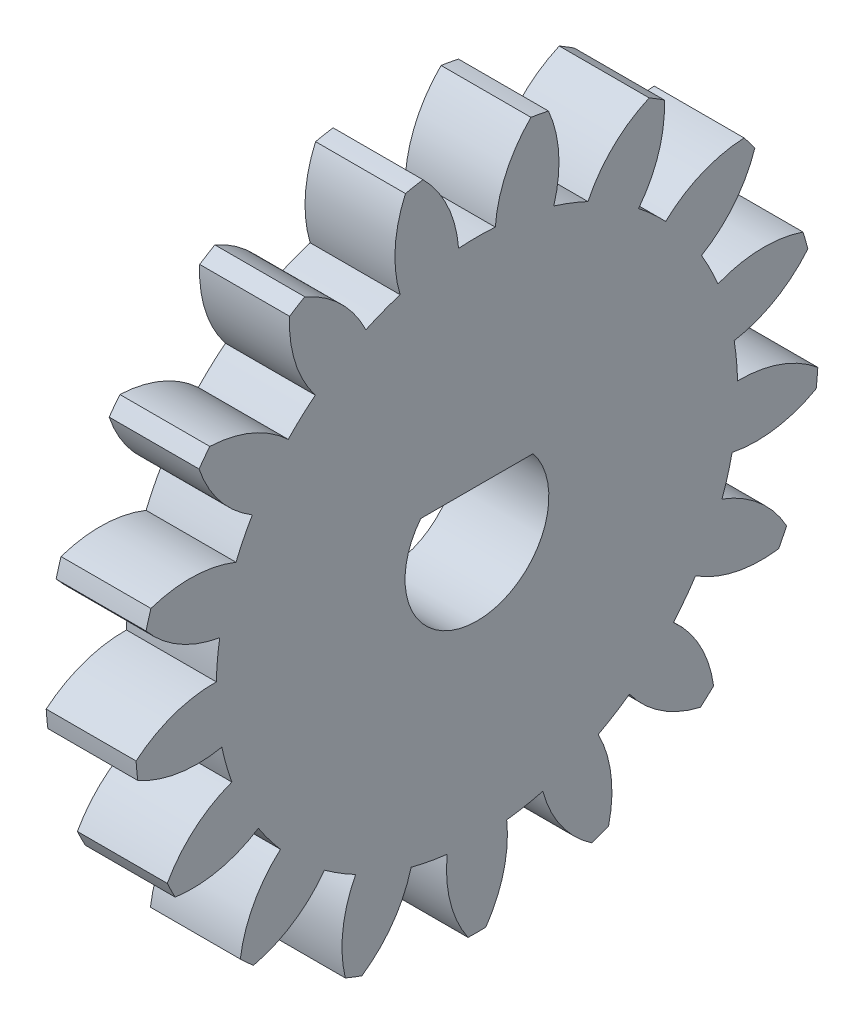
SolidWorks part; units mm, degrees
ref_plane "Plane1" through (0, 0, 0) normal (0, 0, 1) x (1, 0, 0)
ref_plane "Plane2" through (0, 0, 0) normal (0, 1, 0) x (1, 0, 0)
ref_plane "Plane3" through (0, 0, 0) normal (1, 0, 0) x (0, 0, -1)
sketch "HoldingSke" plane through (0, 0, 0) normal (0, 1, 0) x (1, 0, 0)
  line L0 (0, 0) -> (0.4782, -0.1462)
  line L1 (-15, 0) -> (100, 0) construction
  line L2 (0, 0) -> (-2.1039, 2.3779)
  line L3 (0, 0) -> (-11.863, 4.5341)
  line L4 (0, 0) -> (8.2586, 2.5249)
  line L5 (0, 0) -> (-46.8476, -17.4728)
  line L6 (0, 0) -> (-4.1448, -2.7965)
  line L7 (-2.1039, 2.3779) -> (8.6586, 51.2059)
  line L8 (-76.2, 54.61) -> (-74.8, 54.61)
  line L9 (-71.009, 38.7566) -> (-53.1078, 45.2721)
  line L10 (-76.2, 71.12) -> (104.1128, 71.12)
  line L11 (0, 0) -> (-5, 0)
  line L12 (-76.2, 101.6) -> (-76.133, 101.6)
  line L13 (24.9733, 27.94) -> (52.9518, 28.4284)
  line L14 (24.9733, 27.94) -> (24.9743, 27.94)
  line L15 (24.9733, 27.94) -> (100.4006, 29.5858)
  line L16 (-63.627, -2) -> (-12.827, -2)
  circle A0 centre (0, 0) radius 4
  circle A1 centre (0, 0) radius 14.499
  circle A2 centre (0, 0) radius 37.5
  circle A3 centre (0, 0) radius 4
  dimension "MHD" = 28.998
  dimension "Hub_dia" = 75
  dimension "Bore" = 8
  dimension "MBD" = 8
  dimension "Num_teeth" = 17
  dimension "Pitch" = 0.5
  dimension "Overall_len" = 50
  dimension "Show_teeth" = 17
  dimension "Thickness" = 5
  dimension "OAL" = 50.0001
  dimension "T_dim" = 1.4
  dimension "Ap" = 20
  dimension "H" = 19.05
  dimension "Pitch_radius" = 180.3128
  dimension "Width" = 5
  dimension "Backlash" = 0.067
  dimension "Addendum_fac" = 1
  dimension "Dedendum_fac" = 1.25
  dimension "Clearance_fac" = 0.25
  dimension "Dedendum_add" = 0.001
  dimension "Module" = 2
sketch "BasProSke" plane through (0, 0, 0) normal (0, 1, 0) x (1, 0, 0)
  line L0 (-10, 0) -> (60, 0) construction
  line L1 (0, 0) -> (0, 19)
  line L2 (0, 0) -> (5, 0)
  line L3 (5, 0) -> (5, 19)
  line L4 (5, 19) -> (0, 19)
  dimension "Thickness" = 5
  dimension "Diameter" = 38
revolve "Base-Revolve" add sketch "BasProSke" angle 360 about L0
sketch "TooCutSke" plane through (0, 0, 0) normal (1, 0, 0) x (0, 0, -1)
  line L1 (0, 0) -> (0, 107) construction
  line L2 (0, 0) -> (-1.6857, 16.9162) construction
  line L3 (0, 0) -> (-6.2247, 33.2991) construction
  line L4 (-1.6857, 16.9162) -> (-3.1123, 16.6495) construction
  arc A0 (1.0204, 14.4631) -> (-1.0204, 14.4631) centre (0, 0) ccw
  arc A1 (3.0261, 18.7832) -> (-3.0261, 18.7832) centre (0, 0) ccw
  circle A2 centre (0, 0) radius 17 construction
  circle A3 centre (0, 0) radius 15.9748 construction
  arc A4 (-1.0204, 14.4631) -> (-3.0261, 18.7832) centre (-7.8003, 13.9409) ccw
  arc A5 (3.0261, 18.7832) -> (1.0204, 14.4631) centre (7.8003, 13.9409) ccw
  dimension "Root_dia" = 28.998
  dimension "Overcut_dia" = 38.0508
  dimension "Pitch_dia" = 34
  dimension "Base_dia" = 31.9495
  dimension "Flank_rad" = 6.8
  dimension "Half_ang" = 10.588
  dimension "Half_CT" = 1.4513
extrude "ToothCut" cut sketch "TooCutSke" along normal through all
fillet "Breaks" [suppressed] radius 0.04
fillet "RootFillets" [suppressed] radius 0.501
pattern_circular "TeethCuts" count 17 every 21.176 about axis through (-10, 0, 0) along (1, 0, 0) of "ToothCut", "RootFillets", "Breaks"
sketch "HubNeaOneSke" plane through (0, 0, 0) normal (-1, 0, 0) x (0, 0, 1)
  circle A0 centre (0, 0) radius 14.499
  dimension "Diameter" = 28.998
extrude "HubNearOne" [suppressed] add sketch "HubNeaOneSke" along normal blind 45.0001
sketch "HubNeaBotSke" plane through (0, 0, 0) normal (-1, 0, 0) x (0, 0, 1)
  circle A0 centre (0, 0) radius 14.499
  dimension "Diameter" = 28.998
extrude "HubNearBoth" [suppressed] add sketch "HubNeaBotSke" along normal blind 22.5
ref_plane "FarPln" through (5, 0, 0) normal (1, 0, 0) x (0, 0, -1)
sketch "HubFarSke" plane through (5, 0, 0) normal (1, 0, 0) x (0, 0, -1)
  circle A0 centre (0, 0) radius 14.499
  dimension "Diameter" = 28.998
extrude "HubFar" [suppressed] add sketch "HubFarSke" along normal blind 22.5
sketch "BorSke" plane through (0, 0, 0) normal (1, 0, 0) x (0, 0, -1)
  circle A0 centre (0, 0) radius 4
  dimension "Diameter" = 8
extrude "Bore" cut sketch "BorSke" along normal mid plane 100.0001
sketch "KeySke" plane through (0, 0, 0) normal (1, 0, 0) x (0, 0, -1)
  line L0 (-1.5, 0) -> (-1.5, 5.4)
  line L1 (-1.5, 5.4) -> (1.5, 5.4)
  line L2 (1.5, 5.4) -> (1.5, 0)
  line L3 (0, 0) -> (0, 34) construction
  line L4 (-1.5, 0) -> (1.5, 0)
  dimension "Offset" = 5.4
  dimension "Width" = 3
extrude "Keyway" [suppressed] cut sketch "KeySke" along normal mid plane 100.0001
pattern_circular "Keyway2" [suppressed] count 2 every 90 about axis through (-10, 0, 0) along (1, 0, 0)
sketch "Sketch1" plane through (0, 0, 0) normal (-1, 0, 0) x (0, 0, 1)
  line L0 (-3.1225, 2.5) -> (3.1225, 2.5)
  circle A0 centre (0, 0) radius 4
  dimension "D2" = 8
  dimension "D1" = 2.5
extrude "Boss-Extrude1" add sketch "Sketch1" against normal blind 5 contours L0 A0
equation "' \"Module@HoldingSke\" = 6.35"
equation "' \"Num_teeth@HoldingSke\" = 12"
equation "' \"Ap@HoldingSke\" =  20"
equation "' \"Ap@HoldingSke\" = 20"
equation "' \"Width@HoldingSke\" = 0.5 * 25.4"
equation "' \"Hub_dia@HoldingSke\"= 1 * 25.4"
equation "' \"Hub_dia@HoldingSke\" = 1 * 25.4"
equation "' \"Overall_len@HoldingSke\" = 1.0 * 25.4"
equation "' \"Bore@HoldingSke\" = 0.75 * 25.4"
equation "' \"T_dim@HoldingSke\" = 0.1 * 25.4"
equation "' \"Width@KeySke\" = 0.25 * 25.4"
equation "' \"Show_teeth@HoldingSke\" = 13"
equation "' \"Backlash@HoldingSke\" = 0.009 * 25.4"
equation "' \"Addendum_fac@HoldingSke\" = 1.0"
equation "' \"Dedendum_fac@HoldingSke\" = 1.25"
equation "' \"Dedendum_add@HoldingSke\" = 0.00005 * 25.4"
equation "' \"Clearance_fac@HoldingSke\" = 0.25"
equation "\"Pitch@HoldingSke\" = 1 / \"Module@HoldingSke\""
equation "\"Overcut_dia@TooCutSke\" = (\"Num_teeth@HoldingSke\" + 2 * \"Addendum_fac@HoldingSke\") / \"Pitch@HoldingSke\" + 0.002 * 25.4"
equation "\"Pitch_dia@TooCutSke\" = \"Num_teeth@HoldingSke\" / \"Pitch@HoldingSke\""
equation "\"Base_dia@TooCutSke\" = \"Num_teeth@HoldingSke\" / \"Pitch@HoldingSke\" * cos((\"Ap@HoldingSke\"  * 3.14159265 / 180))"
equation "\"Root_dia@TooCutSke\" = (\"Num_teeth@HoldingSke\" + 2) / \"Pitch@HoldingSke\" - 2 * (\"Addendum_fac@HoldingSke\" + \"Dedendum_fac@HoldingSke\") / \"Pitch@HoldingSke\" - \"Dedendum_add@HoldingSke\" * 2"
equation "\"Half_ang@TooCutSke\" = 180 / \"Num_teeth@HoldingSke\""
equation "\"Half_CT@TooCutSke\" = \"Num_teeth@HoldingSke\" / \"Pitch@HoldingSke\" * sin((3.14159265 / 2 / \"Num_teeth@HoldingSke\")) / 2 - 7 * \"Backlash@HoldingSke\" / 4"
equation "\"Flank_rad@TooCutSke\" = \"Num_teeth@HoldingSke\" / \"Pitch@HoldingSke\" / 5"
equation "\"Radius@RootFillets\" = \"Clearance_fac@HoldingSke\" / \"Pitch@HoldingSke\" + \"Dedendum_add@HoldingSke\""
equation "\"Break_rad@Breaks\" = 0.02 / \"Pitch@HoldingSke\""
equation "\"Thickness@HoldingSke\" = \"Width@HoldingSke\""
equation "\"OAL@HoldingSke\" = \"Thickness@HoldingSke\""
equation "\"MHD@HoldingSke\" = (\"Num_teeth@HoldingSke\" + 2) / \"Pitch@HoldingSke\" - 2 * (\"Addendum_fac@HoldingSke\" + \"Dedendum_fac@HoldingSke\")  / \"Pitch@HoldingSke\" - \"Dedendum_add@HoldingSke\" * 2"
equation "\"MBD@HoldingSke\" = (\"Num_teeth@HoldingSke\" + 2) / \"Pitch@HoldingSke\" - 2 * (\"Addendum_fac@HoldingSke\" + \"Dedendum_fac@HoldingSke\")  / \"Pitch@HoldingSke\" - \"Dedendum_add@HoldingSke\" * 2 - 0.002 * 25.4"
equation "\"MHD@HoldingSke\" = ((sgn( \"MHD@HoldingSke\" - \"Hub_dia@HoldingSke\" )-1)*( \"MHD@HoldingSke\" - \"Hub_dia@HoldingSke\" ))/-2+ \"Hub_dia@HoldingSke\""
equation "\"MBD@HoldingSke\" = ((sgn( \"MBD@HoldingSke\" - \"Bore@HoldingSke\" )-1)*( \"MBD@HoldingSke\" - \"Bore@HoldingSke\" ))/-2+ \"Bore@HoldingSke\""
equation "\"OAL@HoldingSke\" = ((sgn( \"OAL@HoldingSke\" - \"Overall_len@HoldingSke\" )+1)*( \"OAL@HoldingSke\" - \"Overall_len@HoldingSke\" ))/2 + \"Overall_len@HoldingSke\" + 0.000002 * 25.4"
equation "\"Num_teeth@TeethCuts\" = int( \"Show_teeth@HoldingSke\" ) + 1"
equation "\"Num_teeth@TeethCuts\" = ((sgn( \"Num_teeth@TeethCuts\" - \"Num_teeth@HoldingSke\" )-1)*( \"Num_teeth@TeethCuts\" - \"Num_teeth@HoldingSke\" ))/-2+ \"Num_teeth@HoldingSke\""
equation "\"Num_teeth@TeethCuts\" = ((sgn( \"Num_teeth@TeethCuts\" - 2.0)+1)*( \"Num_teeth@TeethCuts\" - 2.0))/2 +2.0"
equation "\"Angle@TeethCuts\" = 360.0 / \"Num_teeth@HoldingSke\""
equation "\"Diameter@BasProSke\" = (\"Num_teeth@HoldingSke\" + 2 * \"Addendum_fac@HoldingSke\") / \"Pitch@HoldingSke\""
equation "\"Thickness@BasProSke\"  = \"Thickness@HoldingSke\""
equation "' \"Fillet_rad@BasProSke\" =  \"Thickness@HoldingSke\" * 0.05"
equation "' \"Fillet_rad@BasProSke\" = \"Thickness@HoldingSke\" * 0.05"
equation "\"MHD@HoldingSke\" = ((sgn( \"MHD@HoldingSke\" - \"Root_dia@TooCutSke\" )-1)*( \"MHD@HoldingSke\" - \"Root_dia@TooCutSke\" ))/-2+ \"Root_dia@TooCutSke\""
equation "\"Diameter@HubNeaOneSke\" = \"MHD@HoldingSke\""
equation "\"Length@HubNearOne\" = \"OAL@HoldingSke\" - \"Thickness@BasProSke\""
equation "\"Diameter@HubNeaBotSke\" = \"MHD@HoldingSke\""
equation "\"Length@HubNearBoth\" = ( \"OAL@HoldingSke\" - \"Thickness@BasProSke\" ) / 2.0"
equation "\"Thickness@FarPln\" = \"Thickness@BasProSke\""
equation "\"Diameter@HubFarSke\" = \"MHD@HoldingSke\""
equation "\"Length@HubFar\" = ( \"OAL@HoldingSke\" - \"Thickness@BasProSke\" ) / 2.0"
equation "\"Diameter@BorSke\" = \"MBD@HoldingSke\""
equation "\"D1@Bore\" = \"OAL@HoldingSke\" * 2.0"
equation "\"D1@Keyway\" = \"OAL@HoldingSke\" * 2.0"
equation "\"Offset@KeySke\" = \"T_dim@HoldingSke\" + \"MBD@HoldingSke\" / 2.0"
